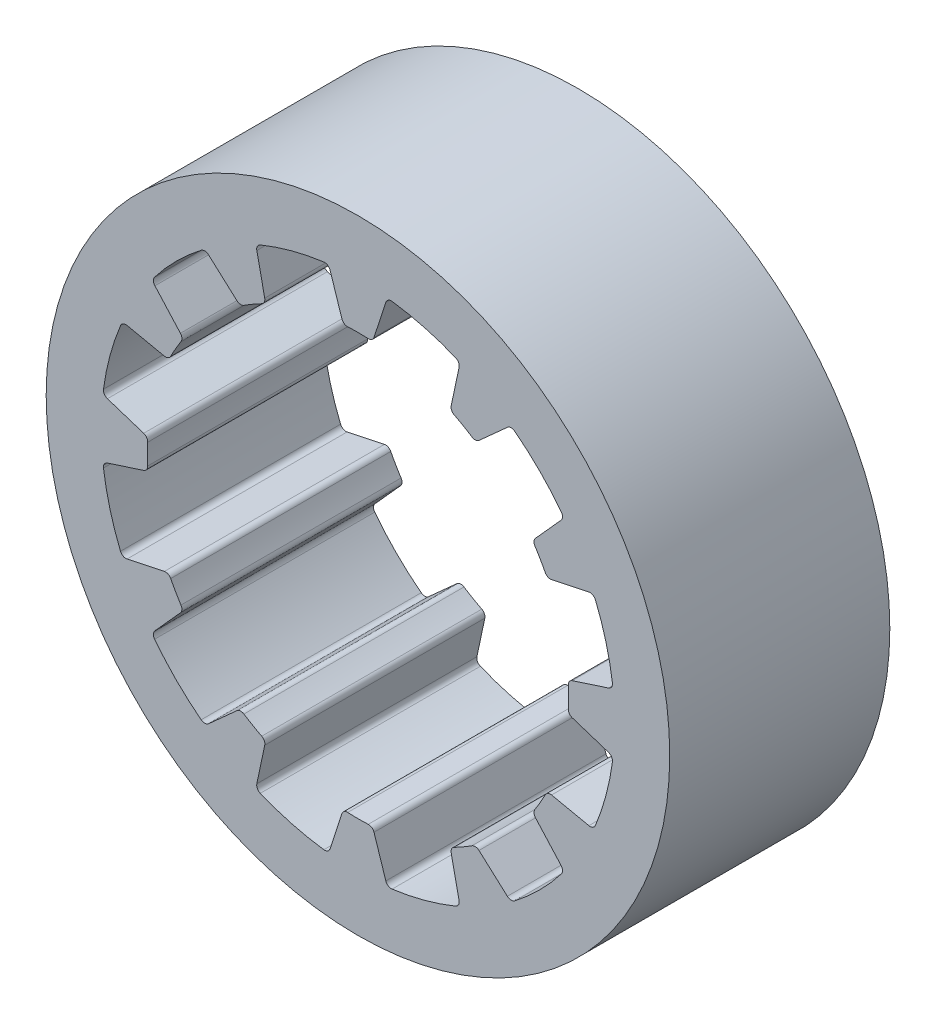
SolidWorks part; units mm, degrees
ref_plane "Front Plane" through (0, 0, 0) normal (0, 0, 1) x (1, 0, 0)
ref_plane "Top Plane" through (0, 0, 0) normal (0, 1, 0) x (1, 0, 0)
ref_plane "Right Plane" through (0, 0, 0) normal (1, 0, 0) x (0, 0, -1)
sketch "Model" plane through (0, 0, 0) normal (0, 0, 1) x (1, 0, 0)
  line L0 (-8.0705, 16.7577) -> (-8.7545, 19.9877)
  line L1 (-12.9326, 17.5755) -> (-10.4773, 15.3681)
  line L2 (-15.3681, 10.4773) -> (-17.5755, 12.9326)
  line L3 (-19.9877, 8.7545) -> (-16.7577, 8.0705)
  line L4 (-18.5478, 1.3896) -> (-21.6871, 2.4122)
  line L5 (-21.6871, -2.4122) -> (-18.5478, -1.3896)
  line L6 (-16.7577, -8.0705) -> (-19.9877, -8.7545)
  line L7 (-17.5755, -12.9326) -> (-15.3681, -10.4773)
  line L8 (-10.4773, -15.3681) -> (-12.9326, -17.5755)
  line L9 (-8.7545, -19.9877) -> (-8.0705, -16.7577)
  line L10 (-1.3896, -18.5478) -> (-2.4122, -21.6871)
  line L11 (2.4122, -21.6871) -> (1.3896, -18.5478)
  line L12 (8.0705, -16.7577) -> (8.7545, -19.9877)
  line L13 (12.9326, -17.5755) -> (10.4773, -15.3681)
  line L14 (15.3681, -10.4773) -> (17.5755, -12.9326)
  line L15 (19.9877, -8.7545) -> (16.7577, -8.0705)
  line L16 (18.5478, -1.3896) -> (21.6871, -2.4122)
  line L17 (21.6871, 2.4122) -> (18.5478, 1.3896)
  line L18 (16.7577, 8.0705) -> (19.9877, 8.7545)
  line L19 (17.5755, 12.9326) -> (15.3681, 10.4773)
  line L20 (10.4773, 15.3681) -> (12.9326, 17.5755)
  line L21 (8.7545, 19.9877) -> (8.0705, 16.7577)
  line L22 (1.3896, 18.5478) -> (2.4122, 21.6871)
  line L23 (-2.4122, 21.6871) -> (-1.3896, 18.5478)
  arc A0 (-2.9541, 22.0278) -> (-8.4556, 20.5537) centre (0, 0) ccw
  arc A1 (-8.4556, 20.5537) -> (-8.7545, 19.9877) centre (-8.2654, 20.0913) ccw
  arc A2 (-8.3311, 16.2094) -> (-8.0705, 16.7577) centre (-8.5596, 16.6541) ccw
  arc A3 (-8.3311, 16.2094) -> (-9.8722, 15.3196) centre (0, 0) ccw
  arc A4 (-10.4773, 15.3681) -> (-9.8722, 15.3196) centre (-10.143, 15.7399) ccw
  arc A5 (-12.9326, 17.5755) -> (-13.5722, 17.5996) centre (-13.2669, 17.2037) ccw
  arc A6 (-13.5722, 17.5996) -> (-17.5996, 13.5722) centre (0, 0) ccw
  arc A7 (-17.5996, 13.5722) -> (-17.5755, 12.9326) centre (-17.2037, 13.2669) ccw
  arc A8 (-15.3196, 9.8722) -> (-15.3681, 10.4773) centre (-15.7399, 10.143) ccw
  arc A9 (-15.3196, 9.8722) -> (-16.2094, 8.3311) centre (0, 0) ccw
  arc A10 (-16.7577, 8.0705) -> (-16.2094, 8.3311) centre (-16.6541, 8.5596) ccw
  arc A11 (-19.9877, 8.7545) -> (-20.5537, 8.4556) centre (-20.0913, 8.2654) ccw
  arc A12 (-20.5537, 8.4556) -> (-22.0278, 2.9541) centre (0, 0) ccw
  arc A13 (-22.0278, 2.9541) -> (-21.6871, 2.4122) centre (-21.5322, 2.8876) ccw
  arc A14 (-18.2033, 0.8898) -> (-18.5478, 1.3896) centre (-18.7027, 0.9142) ccw
  arc A15 (-18.2033, 0.8898) -> (-18.2033, -0.8898) centre (0, 0) ccw
  arc A16 (-18.5478, -1.3896) -> (-18.2033, -0.8898) centre (-18.7027, -0.9142) ccw
  arc A17 (-21.6871, -2.4122) -> (-22.0278, -2.9541) centre (-21.5322, -2.8876) ccw
  arc A18 (-22.0278, -2.9541) -> (-20.5537, -8.4556) centre (0, 0) ccw
  arc A19 (-20.5537, -8.4556) -> (-19.9877, -8.7545) centre (-20.0913, -8.2654) ccw
  arc A20 (-16.2094, -8.3311) -> (-16.7577, -8.0705) centre (-16.6541, -8.5596) ccw
  arc A21 (-16.2094, -8.3311) -> (-15.3196, -9.8722) centre (0, 0) ccw
  arc A22 (-15.3681, -10.4773) -> (-15.3196, -9.8722) centre (-15.7399, -10.143) ccw
  arc A23 (-17.5755, -12.9326) -> (-17.5996, -13.5722) centre (-17.2037, -13.2669) ccw
  arc A24 (-17.5996, -13.5722) -> (-13.5722, -17.5996) centre (0, 0) ccw
  arc A25 (-13.5722, -17.5996) -> (-12.9326, -17.5755) centre (-13.2669, -17.2037) ccw
  arc A26 (-9.8722, -15.3196) -> (-10.4773, -15.3681) centre (-10.143, -15.7399) ccw
  arc A27 (-9.8722, -15.3196) -> (-8.3311, -16.2094) centre (0, 0) ccw
  arc A28 (-8.0705, -16.7577) -> (-8.3311, -16.2094) centre (-8.5596, -16.6541) ccw
  arc A29 (-8.7545, -19.9877) -> (-8.4556, -20.5537) centre (-8.2654, -20.0913) ccw
  arc A30 (-8.4556, -20.5537) -> (-2.9541, -22.0278) centre (0, 0) ccw
  arc A31 (-2.9541, -22.0278) -> (-2.4122, -21.6871) centre (-2.8876, -21.5322) ccw
  arc A32 (-0.8898, -18.2033) -> (-1.3896, -18.5478) centre (-0.9142, -18.7027) ccw
  arc A33 (-0.8898, -18.2033) -> (0.8898, -18.2033) centre (0, 0) ccw
  arc A34 (1.3896, -18.5478) -> (0.8898, -18.2033) centre (0.9142, -18.7027) ccw
  arc A35 (2.4122, -21.6871) -> (2.9541, -22.0278) centre (2.8876, -21.5322) ccw
  arc A36 (2.9541, -22.0278) -> (8.4556, -20.5537) centre (0, 0) ccw
  arc A37 (8.4556, -20.5537) -> (8.7545, -19.9877) centre (8.2654, -20.0913) ccw
  arc A38 (8.3311, -16.2094) -> (8.0705, -16.7577) centre (8.5596, -16.6541) ccw
  arc A39 (8.3311, -16.2094) -> (9.8722, -15.3196) centre (0, 0) ccw
  arc A40 (10.4773, -15.3681) -> (9.8722, -15.3196) centre (10.143, -15.7399) ccw
  arc A41 (12.9326, -17.5755) -> (13.5722, -17.5996) centre (13.2669, -17.2037) ccw
  arc A42 (13.5722, -17.5996) -> (17.5996, -13.5722) centre (0, 0) ccw
  arc A43 (17.5996, -13.5722) -> (17.5755, -12.9326) centre (17.2037, -13.2669) ccw
  arc A44 (15.3196, -9.8722) -> (15.3681, -10.4773) centre (15.7399, -10.143) ccw
  arc A45 (15.3196, -9.8722) -> (16.2094, -8.3311) centre (0, 0) ccw
  arc A46 (16.7577, -8.0705) -> (16.2094, -8.3311) centre (16.6541, -8.5596) ccw
  arc A47 (19.9877, -8.7545) -> (20.5537, -8.4556) centre (20.0913, -8.2654) ccw
  arc A48 (20.5537, -8.4556) -> (22.0278, -2.9541) centre (0, 0) ccw
  arc A49 (22.0278, -2.9541) -> (21.6871, -2.4122) centre (21.5322, -2.8876) ccw
  arc A50 (18.2033, -0.8898) -> (18.5478, -1.3896) centre (18.7027, -0.9142) ccw
  arc A51 (18.2033, -0.8898) -> (18.2033, 0.8898) centre (0, 0) ccw
  arc A52 (18.5478, 1.3896) -> (18.2033, 0.8898) centre (18.7027, 0.9142) ccw
  arc A53 (21.6871, 2.4122) -> (22.0278, 2.9541) centre (21.5322, 2.8876) ccw
  arc A54 (22.0278, 2.9541) -> (20.5537, 8.4556) centre (0, 0) ccw
  arc A55 (20.5537, 8.4556) -> (19.9877, 8.7545) centre (20.0913, 8.2654) ccw
  arc A56 (16.2094, 8.3311) -> (16.7577, 8.0705) centre (16.6541, 8.5596) ccw
  arc A57 (16.2094, 8.3311) -> (15.3196, 9.8722) centre (0, 0) ccw
  arc A58 (15.3681, 10.4773) -> (15.3196, 9.8722) centre (15.7399, 10.143) ccw
  arc A59 (17.5755, 12.9326) -> (17.5996, 13.5722) centre (17.2037, 13.2669) ccw
  arc A60 (17.5996, 13.5722) -> (13.5722, 17.5996) centre (0, 0) ccw
  arc A61 (13.5722, 17.5996) -> (12.9326, 17.5755) centre (13.2669, 17.2037) ccw
  arc A62 (9.8722, 15.3196) -> (10.4773, 15.3681) centre (10.143, 15.7399) ccw
  arc A63 (9.8722, 15.3196) -> (8.3311, 16.2094) centre (0, 0) ccw
  arc A64 (8.0705, 16.7577) -> (8.3311, 16.2094) centre (8.5596, 16.6541) ccw
  arc A65 (8.7545, 19.9877) -> (8.4556, 20.5537) centre (8.2654, 20.0913) ccw
  arc A66 (8.4556, 20.5537) -> (2.9541, 22.0278) centre (0, 0) ccw
  arc A67 (2.9541, 22.0278) -> (2.4122, 21.6871) centre (2.8876, 21.5322) ccw
  arc A68 (0.8898, 18.2033) -> (1.3896, 18.5478) centre (0.9142, 18.7027) ccw
  arc A69 (0.8898, 18.2033) -> (-0.8898, 18.2033) centre (0, 0) ccw
  arc A70 (-1.3896, 18.5478) -> (-0.8898, 18.2033) centre (-0.9142, 18.7027) ccw
  arc A71 (-2.4122, 21.6871) -> (-2.9541, 22.0278) centre (-2.8876, 21.5322) ccw
  circle A72 centre (0, 0) radius 10
  circle A73 centre (0, 0) radius 26.9875
  dimension "D3" = 53.975
  dimension "D1" = 0
  dimension "D2" = 0
extrude "Boss-Extrude1" add sketch "Model" along normal blind 19.05 contours A73 A71 L23 A70 A69 A68 L22 A67 A66 A65 L21 A64 A63 A62 L20 A61 A60 A59 L19 A58 A57 A56 L18 A55 A54 A53 L17 A52 A51 A50 L16 A49 A48 A47 L15 A46 A45 A44 L14 A43 A42 A41 L13 A40 A39 A38 L12 A37 A36 A35
